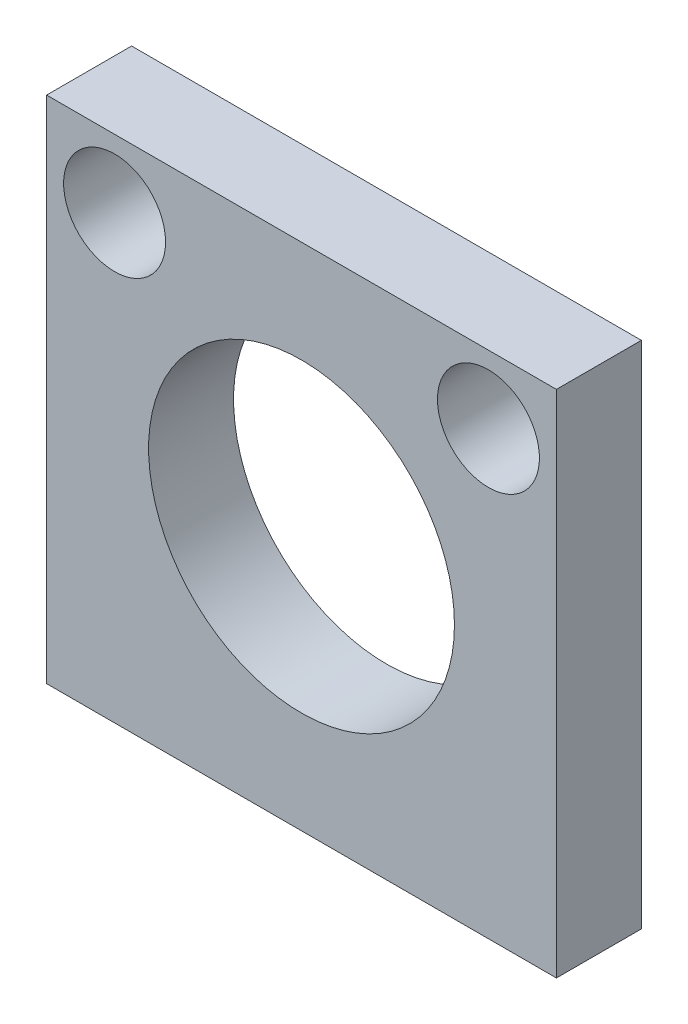
SolidWorks part; units mm, degrees
ref_plane "Alzado" through (0, 0, 0) normal (0, 0, 1) x (1, 0, 0)
ref_plane "Planta" through (0, 0, 0) normal (0, 1, 0) x (1, 0, 0)
ref_plane "Vista lateral" through (0, 0, 0) normal (1, 0, 0) x (0, 0, -1)
sketch "Croquis1" plane through (0, 0, 0) normal (0, 0, 1) x (1, 0, 0)
  line L1 (-15, 15) -> (15, 15)
  line L2 (-15, 15) -> (-15, -15)
  line L3 (-15, -15) -> (15, -15)
  line L4 (15, 15) -> (15, -15)
  line L5 (-15, 15) -> (15, -15) construction
  line L6 (-15, -15) -> (15, 15) construction
  circle A0 centre (-11, 11) radius 3
  circle A1 centre (11, 11) radius 3
  point P0 (0, 0)
  dimension "D3" = 6
  dimension "D1" = 30
  dimension "D2" = 30
  dimension "D4" = 4
  dimension "D5" = 4
extrude "Saliente-Extruir1" add sketch "Croquis1" along normal blind 5
sketch "Croquis2" plane through (0, 0, 5) normal (0, 0, 1) x (1, 0, 0)
  circle A0 centre (0, 0) radius 9
extrude "Cortar-Extruir1" cut sketch "Croquis2" against normal blind 5
